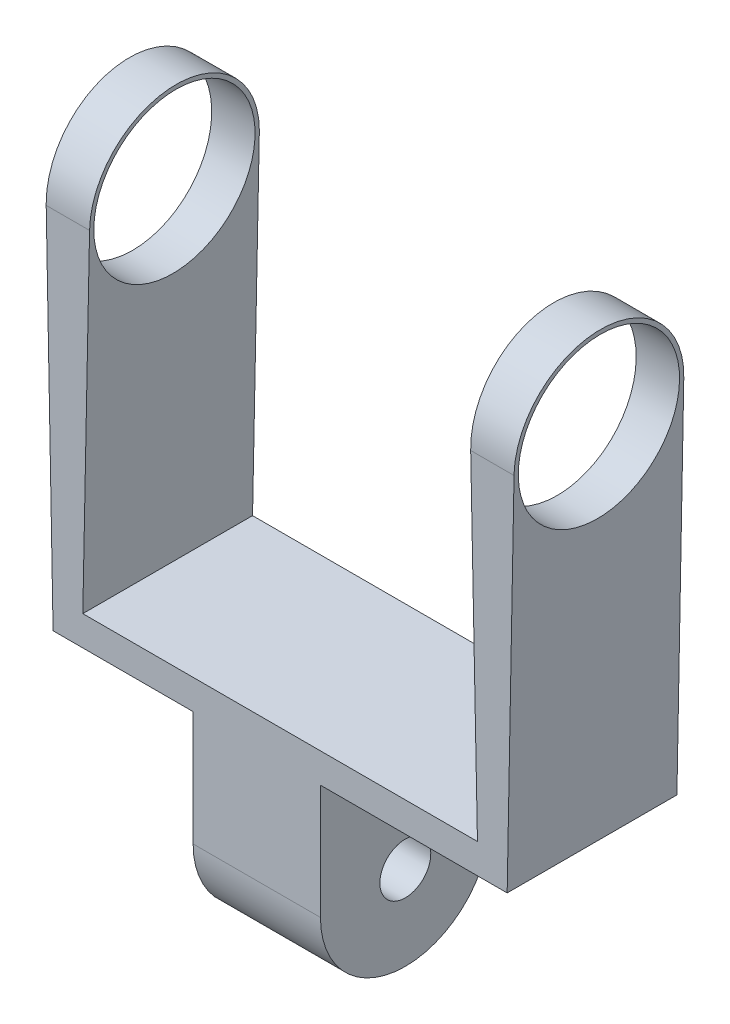
SolidWorks part; units mm, degrees
ref_plane "Plan de face" through (0, 0, 0) normal (0, 0, 1) x (1, 0, 0)
ref_plane "Plan de dessus" through (0, 0, 0) normal (0, 1, 0) x (1, 0, 0)
ref_plane "Plan de droite" through (0, 0, 0) normal (1, 0, 0) x (0, 0, -1)
sketch "Esquisse1" plane through (0, 0, 0) normal (0, 0, 1) x (1, 0, 0)
  line L3 (7, 7) -> (100, 7)
  line L4 (100, 7) -> (98, 106)
  line L5 (98, 106) -> (109, 106)
  line L6 (109, 106) -> (107, 0)
  line L7 (107, 0) -> (0, 0)
  line L8 (103.5, 106) -> (103.5, -19.2234) construction
  line L9 (53.5, 0) -> (53.5, 117.2232) construction
  line L10 (53.5, 0) -> (53.5, 7)
  line L11 (3.5, 106) -> (3.5, -19.2234) construction
  line L12 (-2, 106) -> (0, 0)
  line L13 (9, 106) -> (-2, 106)
  line L14 (7, 7) -> (9, 106)
  dimension "D1" = 7
  dimension "D2" = 107
  dimension "D3" = 3.5
  dimension "D4" = 7
  dimension "D5" = 11
  dimension "D6" = 106
extrude "Boss.-Extru.1" add sketch "Esquisse1" along normal blind 40 contours L14 L13 L12 L7 L6 L5 L4 L3
sketch "Esquisse2" plane through (0, -1.0092, 0) normal (1, 0, 0) x (0, 0, -1)
  line L0 (0, 1.0092) -> (0, 107.0092) construction
  line L1 (-40, 1.0092) -> (-40, 107.0092) construction
  line L2 (-40, 107.0092) -> (0, 107.0092) construction
  line L3 (0, 87.0092) -> (0, 107.0092)
  line L4 (-40, 107.0092) -> (0, 107.0092)
  line L5 (-40, 87.0092) -> (-40, 107.0092)
  circle A0 centre (-20, 87.0092) radius 20
  circle A1 centre (-20, 87.0092) radius 19
  dimension "D2" = 1
  dimension "D1" = 20
extrude "Enlèv. mat.-Extru.1" cut sketch "Esquisse2" against normal through all and the other way through all contours A1 | A0 L4 L5 | A0 L3 L4
sketch "Esquisse3" plane through (0, 0, 0) normal (0, -1, 0) x (1, 0, 0)
  line L0 (0, 40) -> (107, 40) construction
  line L1 (33, 40) -> (63, 40)
  line L2 (33, 40) -> (33, 0)
  line L3 (33, 0) -> (63, 0)
  line L4 (63, 40) -> (63, 0)
  line L5 (0, 0) -> (107, 0) construction
  line L8 (0, 40) -> (0, 0) construction
  dimension "D1" = 33
  dimension "D2" = 30
extrude "Boss.-Extru.2" add sketch "Esquisse3" along normal blind 47
sketch "Esquisse5" plane through (33, 0, 0) normal (-1, 0, 0) x (0, 0, 1)
  line L0 (0, -47) -> (0, 0) construction
  line L1 (40, -47) -> (40, 0) construction
  line L2 (40, -47) -> (0, -47) construction
  line L3 (40, -47) -> (40, -27)
  line L4 (0, -47) -> (0, -27)
  line L5 (40, -47) -> (0, -47)
  circle A0 centre (20, -27) radius 20
  line M3 (0, 0) -> (0, -47)
  line M4 (0, -47) -> (40, -47)
  line M5 (40, -47) -> (40, 0)
extrude "Enlèv. mat.-Extru.2" cut sketch "Esquisse5" against normal through all contours A0 L5 M5 | A0 M3 M4
sketch "Esquisse6" plane through (33, 0, 0) normal (-1, 0, 0) x (0, 0, 1)
  circle A0 centre (20, -27) radius 6
  arc A1 (0, -27) -> (40, -27) centre (20, -27) ccw construction
  dimension "D1" = 14
extrude "Enlèv. mat.-Extru.3" cut sketch "Esquisse6" against normal through all
ref_plane "Plan8" through (107, 0, 0) normal (1, 0, 0) x (0, 0, -1)
